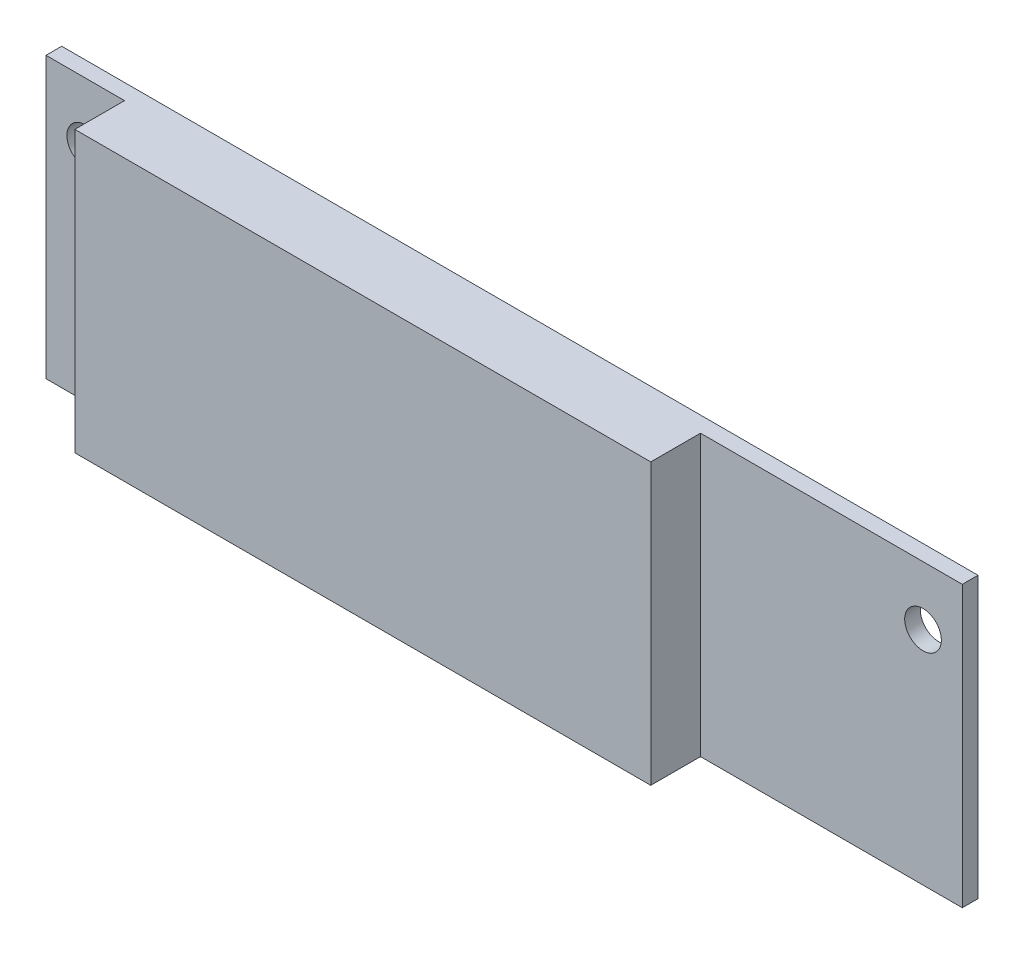
SolidWorks part; units mm, degrees
ref_plane "Front Plane" through (0, 0, 0) normal (0, 0, 1) x (1, 0, 0)
ref_plane "Top Plane" through (0, 0, 0) normal (0, 1, 0) x (1, 0, 0)
ref_plane "Right Plane" through (0, 0, 0) normal (1, 0, 0) x (0, 0, -1)
sketch "Sketch1" plane through (0, 0, 0) normal (0, 0, 1) x (1, 0, 0)
  line L0 (0, 17.7) -> (0, 0) construction
  line L1 (-35, 28.4) -> (35, 28.4)
  line L2 (-35, 28.4) -> (-35, 7)
  line L3 (-35, 7) -> (35, 7)
  line L4 (35, 28.4) -> (35, 7)
  line L5 (-35, 28.4) -> (35, 7) construction
  line L6 (-35, 7) -> (35, 28.4) construction
  line L7 (-25.35, 9) -> (25.35, 9) construction
  point P0 (0, 17.7)
  dimension "D1" = 70
  dimension "D2" = 21.4
  dimension "D3" = 2
extrude "Boss-Extrude1" add sketch "Sketch1" along normal blind 5
sketch "Sketch2" plane through (0, 0, 5) normal (0, 0, 1) x (1, 0, 0)
  line L0 (-35, 7) -> (35, 7) construction
  line L1 (-35, 28.4) -> (-29, 28.4)
  line L2 (-35, 28.4) -> (-35, 7)
  line L3 (-35, 7) -> (-29, 7)
  line L4 (-29, 28.4) -> (-29, 7)
  line L6 (35, 28.4) -> (15, 28.4)
  line L7 (35, 28.4) -> (35, 7)
  line L8 (35, 7) -> (15, 7)
  line L9 (15, 28.4) -> (15, 7)
  dimension "D1" = 6
  dimension "D2" = 20
extrude "Cut-Extrude1" cut sketch "Sketch2" against normal offset from surface (3.8 mm away) 1.2 up to face at (0, 17.7, 0)
sketch "Sketch3" plane through (0, 0, 1.2) normal (0, 0, 1) x (1, 0, 0)
  line L0 (-32, 23.9) -> (32, 23.9) construction
  line L1 (15, 28.4) -> (35, 28.4) construction
  line L2 (35, 28.4) -> (35, 7) construction
  line L3 (-35, 28.4) -> (-29, 28.4) construction
  line L4 (-35, 7) -> (-35, 28.4) construction
  circle A0 centre (32, 23.9) radius 1.4
  circle A1 centre (-32, 23.9) radius 1.4
  dimension "D1" = 2.8
  dimension "D2" = 4.5
  dimension "D3" = 3
  dimension "D4" = 4.5
  dimension "D5" = 3
extrude "Cut-Extrude2" cut sketch "Sketch3" against normal through all
